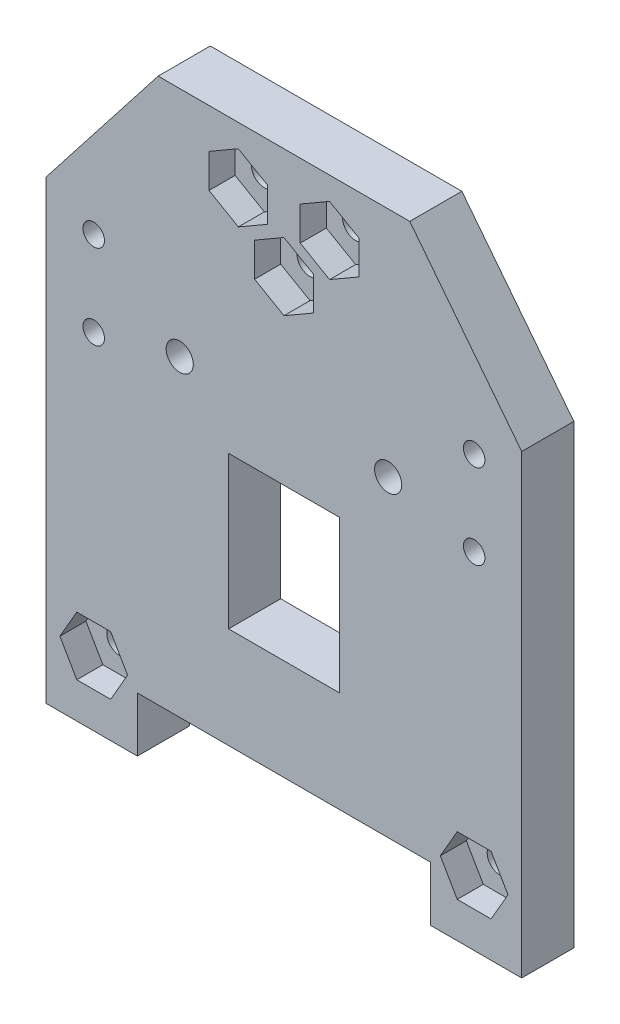
SolidWorks part; units mm, degrees
ref_plane "Plano frontal" through (0, 0, 0) normal (0, 0, 1) x (1, 0, 0)
ref_plane "Plano superior" through (0, 0, 0) normal (0, 1, 0) x (1, 0, 0)
ref_plane "Plano direito" through (0, 0, 0) normal (1, 0, 0) x (0, 0, -1)
sketch "Esboço1" plane through (0, 0, 0) normal (0, 0, 1) x (1, 0, 0)
  line L0 (0, 47.2571) -> (8.5, 47.2571)
  line L1 (0, 47.2571) -> (-8.5, 47.2571)
  line L2 (0, 23.9177) -> (8.5, 23.9177)
  line L3 (0, 23.9177) -> (-8.5, 23.9177)
  line L4 (0, 8.4) -> (0, 75) construction
  line L5 (0, 56.3545) -> (-16, 56.3545) construction
  line L6 (0, 56.3545) -> (16, 56.3545) construction
  line L7 (8.5, 47.2571) -> (8.5, 23.9177)
  line L8 (-8.5, 47.2571) -> (-8.5, 23.9177)
  line L20 (19.3117, 92) -> (-19.3117, 92)
  line L21 (-19.3117, 92) -> (-36.5, 70)
  line L22 (-36.5, 70) -> (-36.5, 0)
  line L23 (-36.5, 0) -> (-22.5, 0)
  line L24 (-22.5, 0) -> (-22.5, 8.4)
  line L25 (-22.5, 8.4) -> (22.5, 8.4)
  line L26 (22.5, 8.4) -> (22.5, 0)
  line L27 (22.5, 0) -> (36.5, 0)
  line L28 (36.5, 0) -> (36.5, 70)
  line L29 (36.5, 70) -> (19.3117, 92)
  circle A13 centre (0, 75) radius 2
  circle A14 centre (-7, 83.3) radius 2
  circle A15 centre (7, 83.3) radius 2
  circle A20 centre (-29.2, 10) radius 2
  circle A21 centre (29.2, 10) radius 2
  circle A26 centre (-16, 56.3545) radius 2.0867
  circle A27 centre (16, 56.3545) radius 2.0867
  point P31 (0, 23.9177)
  point P33 (0, 47.2571)
extrude "Ressalto-extrusão1" add sketch "Esboço1" along normal blind 8
sketch "Esboço3" plane through (0, 0, 8) normal (0, 0, 1) x (1, 0, 0)
  line L0 (-36.5, 70) -> (-36.5, 92) construction
  line L1 (-36.5, 92) -> (-29.2, 92) construction
  line L2 (-19.3117, 92) -> (-36.5, 92) construction
  line L3 (-29.2, 92) -> (-29.2, 66) construction
  circle A0 centre (-29.2, 66) radius 1.3438 construction
sketch "Esboço4" plane through (0, 0, 8) normal (0, 0, 1) x (1, 0, 0)
  line L1 (-29.2, 66) -> (29.2, 66) construction
  line L2 (-29.2, 66) -> (-29.2, 53) construction
  line L3 (-29.2, 53) -> (29.2, 53) construction
  line L4 (29.2, 66) -> (29.2, 53) construction
  circle A0 centre (-29.2, 66) radius 1.65
  circle A1 centre (-29.2, 53) radius 1.65
  circle A2 centre (29.2, 53) radius 1.65
  circle A3 centre (29.2, 66) radius 1.65
extrude "Corte-extrusão1" cut sketch "Esboço4" against normal through all
sketch "Esboço5" plane through (0, 0, 8) normal (0, 0, 1) x (1, 0, 0)
  line L0 (4.5, 72.4019) -> (4.5, 77.5981)
  line L1 (-26.6019, 14.5) -> (-31.7981, 14.5)
  line L2 (-31.7981, 14.5) -> (-34.3962, 10)
  line L3 (-34.3962, 10) -> (-31.7981, 5.5)
  line L4 (-31.7981, 5.5) -> (-26.6019, 5.5)
  line L5 (-26.6019, 5.5) -> (-24.0038, 10)
  line L6 (-24.0038, 10) -> (-26.6019, 14.5)
  line L7 (-11.5, 80.7019) -> (-7, 78.1038)
  line L8 (-7, 78.1038) -> (-2.5, 80.7019)
  line L9 (-2.5, 80.7019) -> (-2.5, 85.8981)
  line L10 (-2.5, 85.8981) -> (-7, 88.4962)
  line L11 (-7, 88.4962) -> (-11.5, 85.8981)
  line L12 (-11.5, 85.8981) -> (-11.5, 80.7019)
  line L13 (4.5, 77.5981) -> (0, 80.1962)
  line L14 (-4.5, 77.5981) -> (-4.5, 72.4019)
  line L15 (0, 69.8038) -> (4.5, 72.4019)
  line L16 (0, 80.1962) -> (-4.5, 77.5981)
  line L17 (-4.5, 72.4019) -> (0, 69.8038)
  line L18 (11.5, 80.7019) -> (11.5, 85.8981)
  line L19 (11.5, 85.8981) -> (7, 88.4962)
  line L20 (2.5, 85.8981) -> (2.5, 80.7019)
  line L21 (7, 78.1038) -> (11.5, 80.7019)
  line L22 (7, 88.4962) -> (2.5, 85.8981)
  line L23 (2.5, 80.7019) -> (7, 78.1038)
  line L24 (31.7981, 5.5) -> (34.3962, 10)
  line L25 (24.0038, 10) -> (26.6019, 5.5)
  line L26 (26.6019, 14.5) -> (24.0038, 10)
  line L27 (34.3962, 10) -> (31.7981, 14.5)
  line L28 (31.7981, 14.5) -> (26.6019, 14.5)
  line L29 (26.6019, 5.5) -> (31.7981, 5.5)
  circle A0 centre (-29.2, 10) radius 4.5 construction
  circle A1 centre (-7, 83.3) radius 4.5 construction
  circle A2 centre (0, 75) radius 4.5 construction
  circle A3 centre (7, 83.3) radius 4.5 construction
  circle A4 centre (29.2, 10) radius 4.5 construction
  dimension "D1" = 9
  dimension "D2" = 9
  dimension "D3" = 9
  dimension "D4" = 9
  dimension "D5" = 9
extrude "Corte-extrusão2" cut sketch "Esboço5" against normal blind 4
